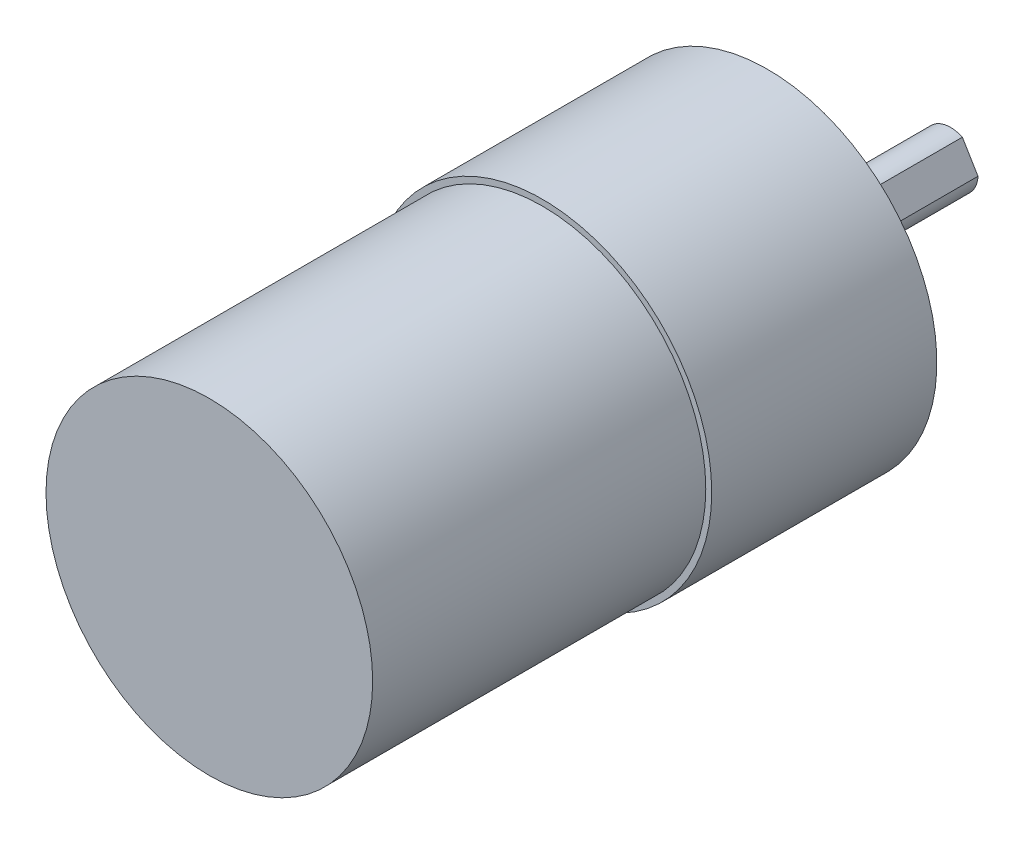
SolidWorks part; units mm, degrees
ref_plane "Front Plane" through (0, 0, 0) normal (0, 0, 1) x (1, 0, 0)
ref_plane "Top Plane" through (0, 0, 0) normal (0, 1, 0) x (1, 0, 0)
ref_plane "Right Plane" through (0, 0, 0) normal (1, 0, 0) x (0, 0, -1)
sketch "Sketch2" plane through (0, 0, 0) normal (0, 0, 1) x (1, 0, 0)
  circle A0 centre (-17.9026, 17.7534) radius 18.5
  dimension "D1" = 37
extrude "Boss-Extrude1" add sketch "Sketch2" along normal blind 81
sketch "Sketch3" plane through (0, 0, 0) normal (0, 0, -1) x (-1, 0, 0)
  circle A0 centre (17.9026, 17.7534) radius 5.9
  circle A2 centre (17.9026, 17.7534) radius 34.5
  circle M3 centre (17.9026, 17.7534) radius 18.5
extrude "Cut-Extrude1" cut sketch "Sketch3" against normal blind 20 contours A0 M3 | A2
sketch "Sketch4" plane through (0, 0, 0) normal (0, 0, -1) x (-1, 0, 0)
  circle A0 centre (17.9026, 17.7534) radius 3
  circle A1 centre (17.9026, 17.7534) radius 5.9
extrude "Cut-Extrude2" cut sketch "Sketch4" against normal blind 15
ref_point "Point1"
sketch "Sketch6" plane through (0, 0, 81) normal (0, 0, 1) x (1, 0, 0)
  circle A0 centre (-17.9026, 17.7534) radius 17.8492
  circle A1 centre (-17.9026, 17.7534) radius 34.5
extrude "Cut-Extrude3" cut sketch "Sketch6" against normal blind 36.4
ref_point "Point2"
sketch "Sketch7" plane through (0, 0, 0) normal (0, 0, -1) x (-1, 0, 0)
  line L0 (17.9026, 17.7534) -> (15.7472, 19.02) construction
sketch "Sketch12" plane through (0, 0, 0) normal (0, 0, -1) x (-1, 0, 0)
  line L0 (15.7472, 19.02) -> (16.6159, 20.4635)
  line L1 (16.6159, 20.4635) -> (14.9055, 17.6215)
  circle A0 centre (17.9026, 17.7534) radius 3
  circle M2 centre (17.9026, 17.7534) radius 3
extrude "Cut-Extrude11" cut sketch "Sketch12" against normal blind 15 contours L1 L0 M2
sketch "Sketch13" plane through (0, 0, 0) normal (0, 0, -1) x (-1, 0, 0)
  line L1 (16.7787, 33.2126) -> (3.9526, 24.5097)
  line L2 (3.9526, 24.5097) -> (5.0764, 9.0505)
  line L3 (5.0764, 9.0505) -> (19.0264, 2.2942)
  line L4 (19.0264, 2.2942) -> (31.8526, 10.9971)
  line L5 (31.8526, 10.9971) -> (30.7287, 26.4563)
  line L6 (30.7287, 26.4563) -> (16.7787, 33.2126)
  circle A0 centre (17.9026, 17.7534) radius 13.4234 construction
  circle A1 centre (3.9526, 24.5097) radius 1.2
  circle A2 centre (16.7787, 33.2126) radius 1.2
  circle A3 centre (30.7287, 26.4563) radius 1.2
  circle A4 centre (31.8526, 10.9971) radius 1.2
  circle A5 centre (19.0264, 2.2942) radius 1.2
  circle A6 centre (5.0764, 9.0505) radius 1.2
  dimension "D2" = 31
extrude "Cut-Extrude13" cut sketch "Sketch13" against normal blind 25.4 contours L1 A1 L2 | L2 A1 L1 | L6 A2 L1 | L3 A6 L2 | L2 A6 L3 | L1 A2 L6 | L5 A3 L6 | L6 A3 L5 | L4 A4 L5 | L5 A4 L4 | L3 A5 L4 | L4 A5 L3
extrude "Cut-Extrude21" cut sketch "Sketch21" against normal through all
sketch "Sketch21" plane through (-74.8833, 44.5722, 212.196) normal (0, 0, 1) x (-0.9785, -0.2064, 0)
  line L16 (-33.2867, 12.7925) -> (-33.2867, 8.2925)
  line L23 (-33.2867, 8.2925) -> (-41.7534, 8.2925)
  line L28 (-58.6867, 12.7925) -> (-33.2867, 12.7925)
  line L31 (-41.7534, 8.2925) -> (-41.7534, 3.1925)
  line L32 (-41.7534, 3.1925) -> (-24.82, 3.1925)
  line L33 (-24.82, 3.1925) -> (-24.82, 60.3425)
  line L34 (-24.82, 60.3425) -> (-75.62, 60.3425)
  line L35 (-75.62, 60.3425) -> (-75.62, 12.7925)
  line L39 (-75.62, 8.2925) -> (-75.62, 3.1925)
  line L40 (-75.62, 3.1925) -> (-58.6867, 3.1925)
  line L41 (-58.6867, 3.1925) -> (-58.6867, 12.7925)
  line L42 (-75.62, 12.7925) -> (-67.1534, 12.7925)
  line L44 (-67.1534, 12.7925) -> (-67.1534, 8.2925)
  line L46 (-67.1534, 8.2925) -> (-75.62, 8.2925)
  circle A1 centre (-50.22, 38.0001) radius 5.9
extrude "Cut-Extrude26" cut sketch "Sketch26" against normal through all
sketch "Sketch26" plane through (-2.1743, -43.2276, 15.2) normal (0, 0, -1) x (-0.3851, -0.9229, 0)
  line L16 (-33.2867, 12.7925) -> (-33.2867, 8.2925)
  line L23 (-33.2867, 8.2925) -> (-41.7534, 8.2925)
  line L28 (-58.6867, 12.7925) -> (-33.2867, 12.7925)
  line L31 (-41.7534, 8.2925) -> (-41.7534, 3.1925)
  line L32 (-41.7534, 3.1925) -> (-24.82, 3.1925)
  line L33 (-24.82, 3.1925) -> (-24.82, 60.3425)
  line L34 (-24.82, 60.3425) -> (-75.62, 60.3425)
  line L35 (-75.62, 60.3425) -> (-75.62, 12.7925)
  line L39 (-75.62, 8.2925) -> (-75.62, 3.1925)
  line L40 (-75.62, 3.1925) -> (-58.6867, 3.1925)
  line L41 (-58.6867, 3.1925) -> (-58.6867, 12.7925)
  line L42 (-75.62, 12.7925) -> (-67.1534, 12.7925)
  line L44 (-67.1534, 12.7925) -> (-67.1534, 8.2925)
  line L46 (-67.1534, 8.2925) -> (-75.62, 8.2925)
  circle A6 centre (-61.8276, 27.728) radius 1.2
  circle A7 centre (-53.3121, 53.1885) radius 1.2
  circle A8 centre (-64.9196, 42.9165) radius 1.2
  circle A9 centre (-47.128, 22.8116) radius 1.2
  circle A10 centre (-35.5204, 33.0836) radius 1.2
  circle A11 centre (-38.6125, 48.2721) radius 1.2
extrude "Cut-Extrude27" cut sketch "Sketch27" against normal through all
sketch "Sketch27" plane through (-74.8833, 44.5722, 212.196) normal (0, 0, 1) x (-0.9785, -0.2064, 0)
  line L16 (-33.2867, 12.7925) -> (-33.2867, 8.2925)
  line L23 (-33.2867, 8.2925) -> (-41.7534, 8.2925)
  line L28 (-58.6867, 12.7925) -> (-33.2867, 12.7925)
  line L31 (-41.7534, 8.2925) -> (-41.7534, 3.1925)
  line L32 (-41.7534, 3.1925) -> (-24.82, 3.1925)
  line L33 (-24.82, 3.1925) -> (-24.82, 60.3425)
  line L34 (-24.82, 60.3425) -> (-75.62, 60.3425)
  line L35 (-75.62, 60.3425) -> (-75.62, 12.7925)
  line L39 (-75.62, 8.2925) -> (-75.62, 3.1925)
  line L40 (-75.62, 3.1925) -> (-58.6867, 3.1925)
  line L41 (-58.6867, 3.1925) -> (-58.6867, 12.7925)
  line L42 (-75.62, 12.7925) -> (-67.1534, 12.7925)
  line L44 (-67.1534, 12.7925) -> (-67.1534, 8.2925)
  line L46 (-67.1534, 8.2925) -> (-75.62, 8.2925)
  circle A6 centre (-61.8276, 27.728) radius 1.2
  circle A7 centre (-53.3121, 53.1885) radius 1.2
  circle A8 centre (-64.9196, 42.9165) radius 1.2
  circle A9 centre (-47.128, 22.8116) radius 1.2
  circle A10 centre (-35.5204, 33.0836) radius 1.2
  circle A11 centre (-38.6125, 48.2721) radius 1.2
